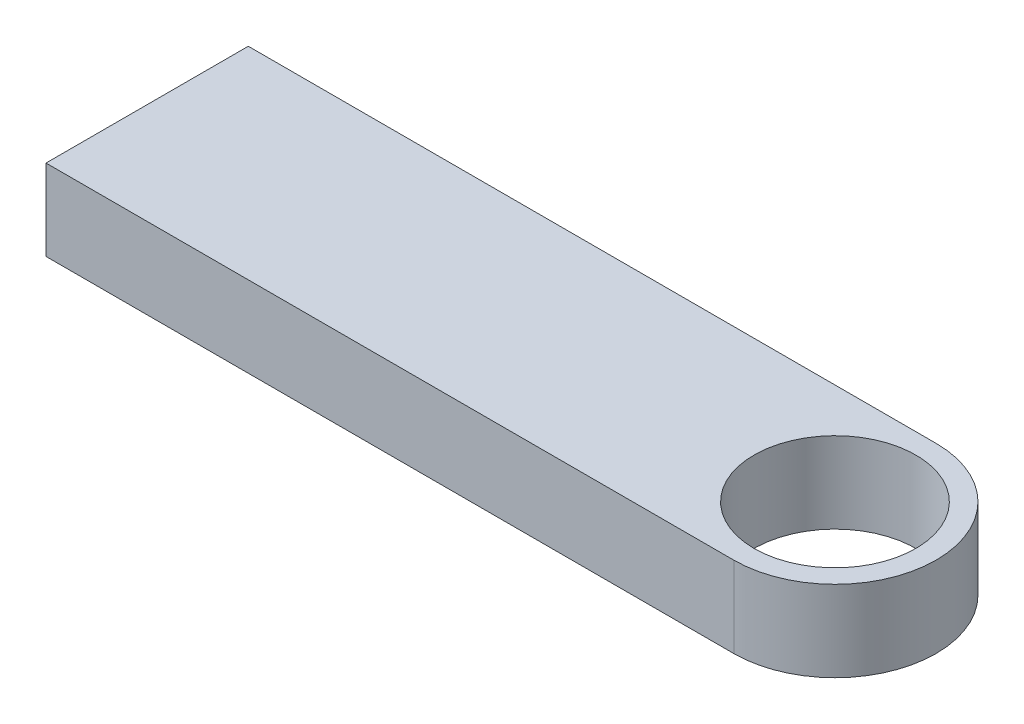
SolidWorks part; units mm, degrees
ref_plane "Спереди" through (0, 0, 0) normal (0, 0, 1) x (1, 0, 0)
ref_plane "Сверху" through (0, 0, 0) normal (0, 1, 0) x (1, 0, 0)
ref_plane "Справа" through (0, 0, 0) normal (1, 0, 0) x (0, 0, -1)
other "Configuration Table"
sketch "Эскиз1" plane through (0, 0, 0) normal (0, 1, 0) x (1, 0, 0)
  line L0 (0, 2.5) -> (-17, 2.5)
  line L1 (-17, 2.5) -> (-17, -2.5)
  line L2 (-17, -2.5) -> (0, -2.5)
  arc A0 (0, -2.5) -> (0, 2.5) centre (0, 0) ccw
  dimension "D1" = 5
  dimension "D2" = 17
extrude "Бобышка-Вытянуть1" add sketch "Эскиз1" along normal blind 2
sketch "Эскиз2" plane through (0, 2, 0) normal (0, 1, 0) x (1, 0, 0)
  circle A0 centre (0, 0) radius 2
  dimension "D1" = 4
extrude "Вырез-Вытянуть1" cut sketch "Эскиз2" against normal blind 3
